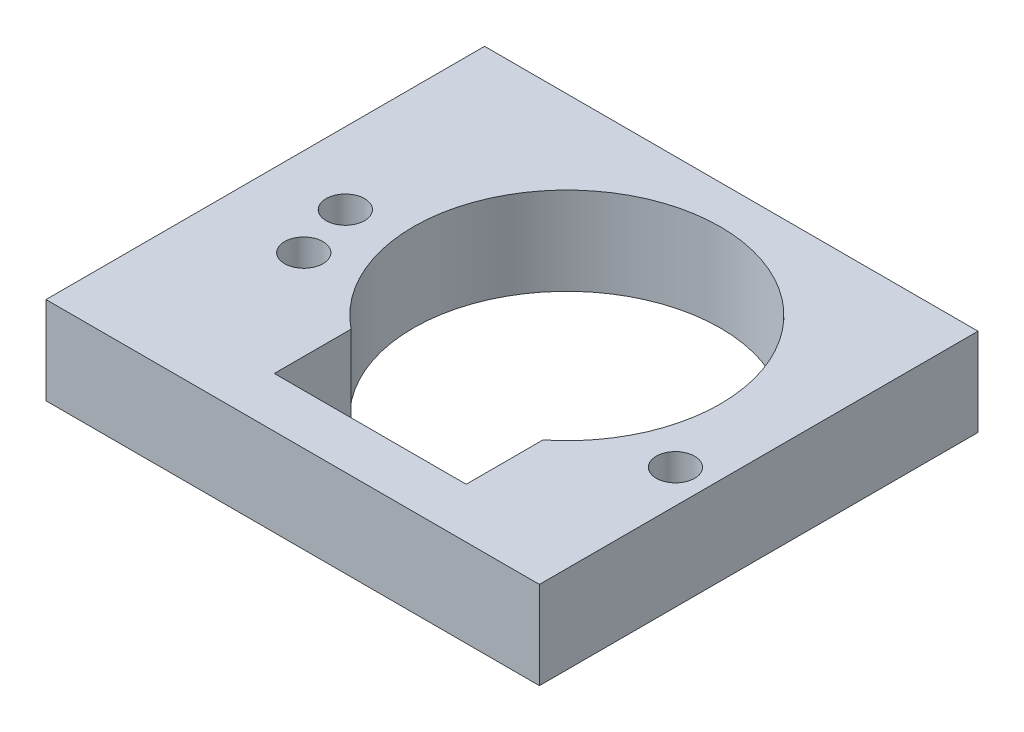
SolidWorks part; units mm, degrees
material "Acrylic (Medium-high impact)"
ref_plane "Front Plane" through (0, 0, 0) normal (0, 0, 1) x (1, 0, 0)
ref_plane "Top Plane" through (0, 0, 0) normal (0, 1, 0) x (1, 0, 0)
ref_plane "Right Plane" through (0, 0, 0) normal (1, 0, 0) x (0, 0, -1)
sketch "Sketch1" plane through (0, 0, 0) normal (0, 1, 0) x (1, 0, 0)
  line L0 (0, 0) -> (-18.45, 0) construction
  line L1 (8.75, -17.9287) -> (8.75, -10.9287)
  line L2 (-8.75, -17.9287) -> (-8.75, -10.9287)
  line L3 (-8.75, -17.9287) -> (8.75, -17.9287)
  line L4 (0, 0) -> (18.45, 0) construction
  line L5 (18.45, -1.75) -> (18.45, -7.0415) construction
  line L6 (18.45, -7.0415) -> (16.95, -7.0415) construction
  line L7 (-18.45, -1.75) -> (-18.45, -7.0415) construction
  line L8 (-18.45, -7.0415) -> (-16.95, -7.0415) construction
  arc A0 (8.75, -10.9287) -> (-8.75, -10.9287) centre (0, 0) ccw
  circle A1 centre (0, 8) radius 2.5 construction
  circle A2 centre (18.45, -1.75) radius 1.75 construction
  circle A3 centre (-18.45, -1.75) radius 1.75
  circle A4 centre (16.95, -7.0415) radius 1.75
  circle A5 centre (-16.95, -7.0415) radius 1.75
  dimension "D1" = 28
  dimension "D2" = 5
  dimension "D6" = 3.5
  dimension "D7" = 40.4
  dimension "D8" = 1.5
  dimension "D9" = 2
  dimension "D10" = 2
  dimension "D3" = 8
  dimension "D4" = 7
  dimension "D5" = 17.5
sketch "Sketch2" plane through (0, 0, 0) normal (0, 1, 0) x (1, 0, 0)
  line L0 (0, 0) -> (-25, 0) construction
  line L1 (-25, 17.5) -> (20, 17.5)
  line L2 (-25, 17.5) -> (-25, -22.5)
  line L3 (-25, -22.5) -> (20, -22.5)
  line L4 (20, 17.5) -> (20, -22.5)
  line L5 (0, 0) -> (20, 0) construction
  line L6 (0, 0) -> (0, 17.5) construction
  line L7 (0, 0) -> (0, -22.5) construction
  circle A0 centre (0, 8) radius 2.5 construction
  dimension "D5" = 5
  dimension "D1" = 45
  dimension "D2" = 40
  dimension "D3" = 17.5
  dimension "D4" = 8
  dimension "D6" = 9.5
  dimension "D7" = 25
  dimension "D8" = 20
  dimension "D9" = 17.5
extrude "Stepper Slider Boss-Extrude1" add sketch "Sketch2" against normal blind 8
extrude "Stepper Hole Cut-Extrude1" cut sketch "Sketch1" against normal up to surface (8 mm away) up to face at (-2.5, -8, 2.5)
